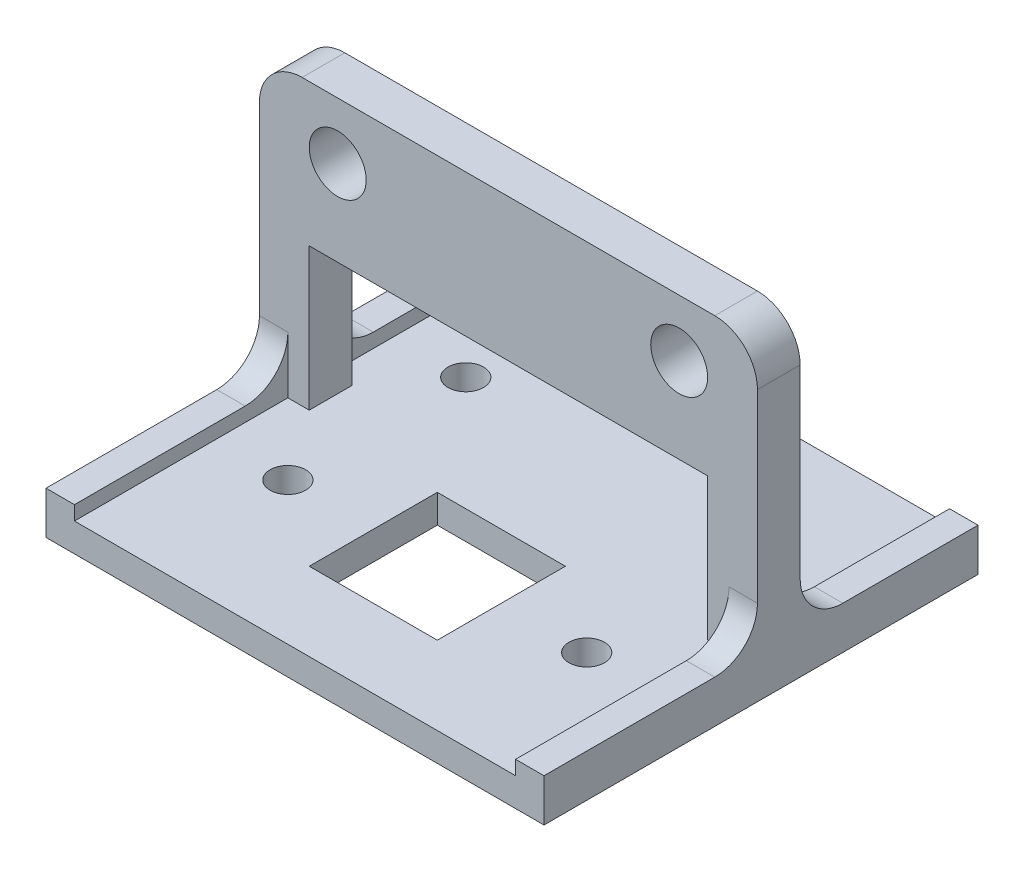
SolidWorks part; units mm, degrees
ref_plane "Front Plane" through (0, 0, 0) normal (0, 0, 1) x (1, 0, 0)
ref_plane "Top Plane" through (0, 0, 0) normal (0, 1, 0) x (1, 0, 0)
ref_plane "Right Plane" through (0, 0, 0) normal (1, 0, 0) x (0, 0, -1)
sketch "Sketch1" plane through (0, 0, 0) normal (0, 1, 0) x (1, 0, 0)
  line L0 (12.5, 24) -> (12.5, 0) construction
  line L1 (0, 0) -> (25, 0) construction
  line L2 (0, 0) -> (0, 24) construction
  line L3 (0, 24) -> (25, 24) construction
  line L4 (25, 0) -> (25, 24) construction
  line L5 (8.5, 13.5) -> (16.5, 13.5) construction
  line L6 (8.5, 13.5) -> (8.5, 5.5) construction
  line L7 (8.5, 5.5) -> (16.5, 5.5) construction
  line L8 (16.5, 13.5) -> (16.5, 5.5) construction
  line L9 (0, 15.75) -> (25, 15.75) construction
  circle A0 centre (2, 22) radius 1 construction
  circle A4 centre (23, 22) radius 1 construction
  circle A5 centre (23, 9.5) radius 1 construction
  circle A6 centre (2, 9.5) radius 1 construction
  point P11 (12.5, 13.5)
  dimension "D6" = 2
  dimension "D1" = 25
  dimension "D2" = 24
  dimension "D3" = 8
  dimension "D4" = 8
  dimension "D5" = 5.5
  dimension "D7" = 2
  dimension "D8" = 2
  dimension "D9" = 6.25
sketch "Sketch2" plane through (0, 0, 0) normal (0, 1, 0) x (1, 0, 0)
  line L0 (12.5, 24) -> (12.5, 0) construction
  line L1 (-2, -2) -> (27, -2)
  line L2 (-2, -2) -> (-2, 26)
  line L3 (-2, 26) -> (27, 26)
  line L4 (27, -2) -> (27, 26)
  line L5 (-2, -2) -> (27, 26) construction
  line L6 (-2, 26) -> (27, -2) construction
  line L7 (0, 0) -> (25, 0) construction
  line L8 (25, 0) -> (25, 24) construction
  point P0 (12.5, 12)
  dimension "D1" = 2
  dimension "D2" = 2
extrude "Boss-Extrude1" [suppressed] add sketch "Sketch2" along normal blind 1
sketch "Sketch3" plane through (0, 0, 0) normal (0, 1, 0) x (1, 0, 0)
  line L0 (16.5, 13.5) -> (16.5, 5.5) construction
  line L1 (8.5, 13.5) -> (16.5, 13.5) construction
  line L2 (8.5, 13.5) -> (8.5, 5.5) construction
  line L3 (8.5, 5.5) -> (16.5, 5.5) construction
  line L4 (16.5, 13.5) -> (16.5, 5.5) construction
  line L5 (8.5, 13.5) -> (16.5, 13.5) construction
  line L6 (8.5, 13.5) -> (8.5, 5.5) construction
  line L7 (8.5, 5.5) -> (16.5, 5.5) construction
  line L8 (8, 14) -> (8, 5)
  line L9 (8, 5) -> (17, 5)
  line L10 (17, 14) -> (17, 5)
  line L11 (8, 14) -> (17, 14)
  circle A0 centre (23, 9.5) radius 1 construction
  circle A1 centre (23, 22) radius 1 construction
  circle A2 centre (2, 22) radius 1 construction
  circle A3 centre (2, 9.5) radius 1 construction
  circle A4 centre (23, 9.5) radius 1 construction
  circle A5 centre (23, 22) radius 1 construction
  circle A6 centre (2, 22) radius 1 construction
  circle A7 centre (2, 9.5) radius 1 construction
  circle A8 centre (2, 9.5) radius 1.5
  circle A9 centre (2, 22) radius 1.5
  circle A10 centre (23, 22) radius 1.5
  circle A11 centre (23, 9.5) radius 1.5
  circle A12 centre (2, 9.5) radius 2
  dimension "D1" = 0.5
  dimension "D2" = 0.5
extrude "Cut-Extrude2" [suppressed] cut sketch "Sketch3" along normal up to next contours A8 | A9 | L5 L4 L7 L6 | A11 | A10 | L8 L9 L10 L11
sketch "Sketch6" [suppressed] plane through (0, 1, 0) normal (0, 1, 0) x (1, 0, 0)
  line L0 (12.5, 24) -> (12.5, 0) construction
  line L5 (12.5, 24) -> (12.5, 12) construction
  line L6 (0, 12) -> (25, 12) construction
  line L7 (0, 0) -> (0, 24) construction
  line L8 (25, 0) -> (25, 24) construction
  circle A0 centre (2, 9.5) radius 1.5 construction
  circle A1 centre (23, 9.5) radius 1.5 construction
  circle A2 centre (23, 22) radius 1.5 construction
  circle A3 centre (2, 22) radius 1.5 construction
  circle A4 centre (2, 9.5) radius 1.5
  circle A5 centre (23, 9.5) radius 1.5
  circle A6 centre (23, 22) radius 1.5
  circle A7 centre (2, 22) radius 1.5
  circle A8 centre (2, 22) radius 2.25
  circle A9 centre (2, 9.5) radius 2.25
  circle A10 centre (23, 9.5) radius 2.25
  circle A11 centre (23, 22) radius 2.25
  point P30 (-1, 25)
  dimension "D1" = 0.75
extrude "Boss-Extrude3" [suppressed] add sketch "Sketch6" along normal blind 4
sketch "Sketch8" [suppressed] plane through (0, 5, 0) normal (0, 1, 0) x (1, 0, 0)
  line L4 (27, -2) -> (27, 26)
  line L5 (27, 26) -> (-2, 26)
  line L6 (-2, 26) -> (-2, -2)
  line L7 (-2, -2) -> (27, -2)
  line L8 (27, -2) -> (27, 26)
  line L9 (27, 26) -> (-2, 26)
  line L10 (-2, 26) -> (-2, -2)
  line L11 (-2, -2) -> (27, -2)
  dimension "D1" = 0
extrude "Boss-Extrude4" [suppressed] add sketch "Sketch8" along normal blind 1
split "Split2" [suppressed] bodies to split 105
sketch "Sketch9" plane through (0, 0, 0) normal (0, 1, 0) x (1, 0, 0)
  line L0 (25, 0) -> (25, 24) construction
  line L1 (0, 0) -> (25, 0) construction
  line L2 (0, 0) -> (0, 24) construction
  line L3 (0, 24) -> (25, 24) construction
  line L4 (25, 0) -> (25, 24) construction
  line L5 (0, 0) -> (25, 0) construction
  line L6 (0, 0) -> (0, 24) construction
  line L7 (0, 24) -> (25, 24) construction
  line L8 (30, -0.5) -> (30, 30)
  line L9 (-5, 30) -> (30, 30)
  line L10 (-5, -0.5) -> (-5, 30)
  line L11 (-5, -0.5) -> (30, -0.5)
  line L12 (16.5, 13.5) -> (16.5, 5.5) construction
  line L13 (8.5, 13.5) -> (16.5, 13.5) construction
  line L14 (8.5, 5.5) -> (16.5, 5.5) construction
  line L15 (8.5, 13.5) -> (8.5, 5.5) construction
  line L16 (16.5, 13.5) -> (16.5, 5.5) construction
  line L17 (8.5, 13.5) -> (16.5, 13.5) construction
  line L18 (8.5, 5.5) -> (16.5, 5.5) construction
  line L19 (8.5, 13.5) -> (8.5, 5.5) construction
  line L20 (17, 14) -> (17, 5)
  line L21 (8, 5) -> (17, 5)
  line L22 (8, 14) -> (8, 5)
  line L23 (8, 14) -> (17, 14)
  dimension "D3" = 6
  dimension "D1" = 5
  dimension "D4" = 5
  dimension "D5" = 0.5
  dimension "D2" = 0.5
extrude "Boss-Extrude5" add sketch "Sketch9" along normal blind 2
sketch "Sketch10" plane through (0, 2, 0) normal (0, 1, 0) x (1, 0, 0)
  line L0 (25, 0) -> (25, 24) construction
  line L1 (0, 0) -> (25, 0) construction
  line L2 (0, 0) -> (0, 24) construction
  line L3 (0, 24) -> (25, 24) construction
  line L4 (25, 0) -> (25, 24) construction
  line L5 (0, 0) -> (25, 0) construction
  line L6 (0, 0) -> (0, 24) construction
  line L7 (0, 24) -> (25, 24) construction
  line L8 (28, -0.5) -> (28, 28)
  line L9 (-3, 28) -> (28, 28)
  line L10 (-3, -0.5) -> (-3, 28)
  line L12 (-5, -0.5) -> (30, -0.5)
  line L13 (30, -0.5) -> (30, 30)
  line L14 (30, 30) -> (-5, 30)
  line L15 (-5, 30) -> (-5, -0.5)
  line L16 (-5, -0.5) -> (-3, -0.5)
  line L17 (30, -0.5) -> (30, 30)
  line L18 (30, 30) -> (-5, 30)
  line L19 (-5, 30) -> (-5, -0.5)
  line L20 (28, -0.5) -> (30, -0.5)
  dimension "D2" = 2
  dimension "D3" = 2
  dimension "D4" = 2
  dimension "D1" = 0
extrude "Boss-Extrude6" add sketch "Sketch10" along normal blind 1
sketch "Sketch12" plane through (0, 2, 0) normal (0, 1, 0) x (1, 0, 0)
  circle A0 centre (23, 9.5) radius 1 construction
  circle A1 centre (23, 22) radius 1 construction
  circle A2 centre (2, 22) radius 1 construction
  circle A3 centre (2, 9.5) radius 1 construction
  circle A4 centre (23, 9.5) radius 1 construction
  circle A5 centre (23, 22) radius 1 construction
  circle A6 centre (2, 22) radius 1 construction
  circle A7 centre (2, 9.5) radius 1 construction
  circle A8 centre (2, 22) radius 1.25
  circle A9 centre (2, 9.5) radius 1.25
  circle A10 centre (23, 9.5) radius 1.25
  circle A11 centre (23, 22) radius 1.25
  dimension "D1" = 0.25
extrude "Cut-Extrude4" cut sketch "Sketch12" against normal up to next
ref_plane "Plane2" through (0, 0, -17.5) normal (0, 0, -1) x (-1, 0, 0)
sketch "Sketch16" plane through (0, 0, -17.5) normal (0, 0, 1) x (1, 0, 0)
  line L0 (12.5, 22) -> (12.5, 2) construction
  line L1 (-5, 0) -> (30, 0)
  line L2 (-5, 0) -> (-5, 22)
  line L3 (-5, 22) -> (30, 22)
  line L4 (30, 0) -> (30, 22)
  line L5 (-3, 2) -> (28, 2) construction
  line L8 (-1.5, 2) -> (-1.5, 12)
  line L9 (-1.5, 12) -> (26.5, 12)
  line L10 (26.5, 2) -> (26.5, 12)
  line L11 (-1.5, 2) -> (26.5, 2)
  line L12 (-3, 2) -> (28, 2) construction
  circle A0 centre (0.5, 18) radius 2
  circle A1 centre (24.5, 18) radius 2
  point P19 (12.5, 12)
  dimension "D2" = 4
  dimension "D1" = 18
  dimension "D3" = 4
  dimension "D4" = 5.5
  dimension "D5" = 10
  dimension "D6" = 28
extrude "Boss-Extrude9" add sketch "Sketch16" along normal blind 3
sketch "Sketch17" plane through (0, 0, -28) normal (0, 0, 1) x (1, 0, 0)
  line L4 (-3, 2) -> (28, 2)
  line L5 (28, 2) -> (28, 3)
  line L6 (28, 3) -> (-3, 3)
  line L7 (-3, 3) -> (-3, 2)
  line L8 (-3, 2) -> (28, 2)
  line L9 (28, 2) -> (28, 3)
  line L10 (28, 3) -> (-3, 3)
  line L11 (-3, 3) -> (-3, 2)
  dimension "D1" = 0
extrude "Cut-Extrude8" cut sketch "Sketch17" against normal through all
fillet "Fillet3" radius 3 6 edges at (29, 3, -14.5) (-4, 3, -14.5) (-4, 3, -17.5) (29, 3, -17.5) (30, 22, -16) (-5, 22, -16)
